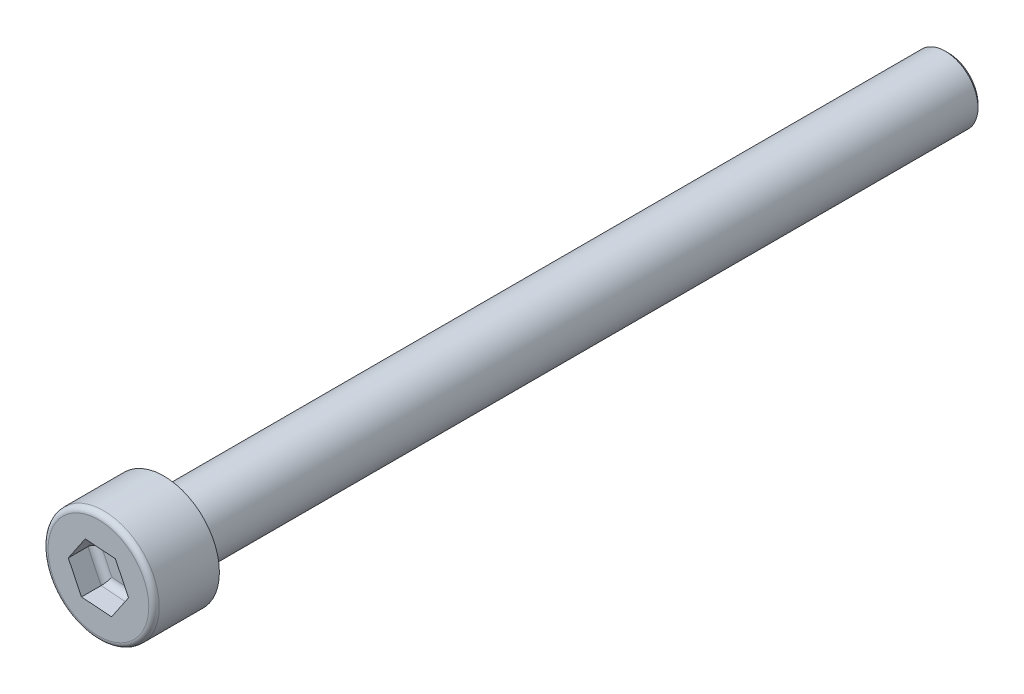
SolidWorks part; units mm, degrees
ref_plane "Ön Düzlem" through (0, 0, 0) normal (0, 0, 1) x (1, 0, 0)
ref_plane "Üst Düzlem" through (0, 0, 0) normal (0, 1, 0) x (1, 0, 0)
ref_plane "Sağ Düzlem" through (0, 0, 0) normal (1, 0, 0) x (0, 0, -1)
sketch "Sketch1" plane through (0, 0, 0) normal (0, 0, 1) x (1, 0, 0)
  circle A0 centre (0, 0) radius 2.5
  dimension "D1" = 5
extrude "Boss-Extrude1" add sketch "Sketch1" along normal blind 60
sketch "Sketch2" plane through (0, 0, 60) normal (0, 0, 1) x (1, 0, 0)
  circle A0 centre (0, 0) radius 4.25
  dimension "D1" = 8.5
extrude "Boss-Extrude2" add sketch "Sketch2" along normal blind 5
sketch "Sketch3" plane through (0, 0, 65) normal (0, 0, 1) x (1, 0, 0)
  line L1 (2.3035, -0.1655) -> (1.2951, 1.9121)
  line L2 (1.2951, 1.9121) -> (-1.0084, 2.0776)
  line L3 (-1.0084, 2.0776) -> (-2.3035, 0.1655)
  line L4 (-2.3035, 0.1655) -> (-1.2951, -1.9121)
  line L5 (-1.2951, -1.9121) -> (1.0084, -2.0776)
  line L6 (1.0084, -2.0776) -> (2.3035, -0.1655)
  circle A0 centre (0, 0) radius 2 construction
  dimension "D1" = 2
extrude "Cut-Extrude1" cut sketch "Sketch3" against normal blind 2
fillet "Fillet1" radius 0.4 1 edges at (4.25, 0, 65)
chamfer "Chamfer1" distance 0.25 angle 45 1 edges at (2.5, 0, 0)
fillet "Fillet2" radius 0.5 6 edges at (-0.1434, -1.9949, 63) (-1.7993, -0.8733, 63) (-1.6559, 1.1216, 63) (0.1434, 1.9949, 63) (1.7993, 0.8733, 63) (1.6559, -1.1216, 63)
